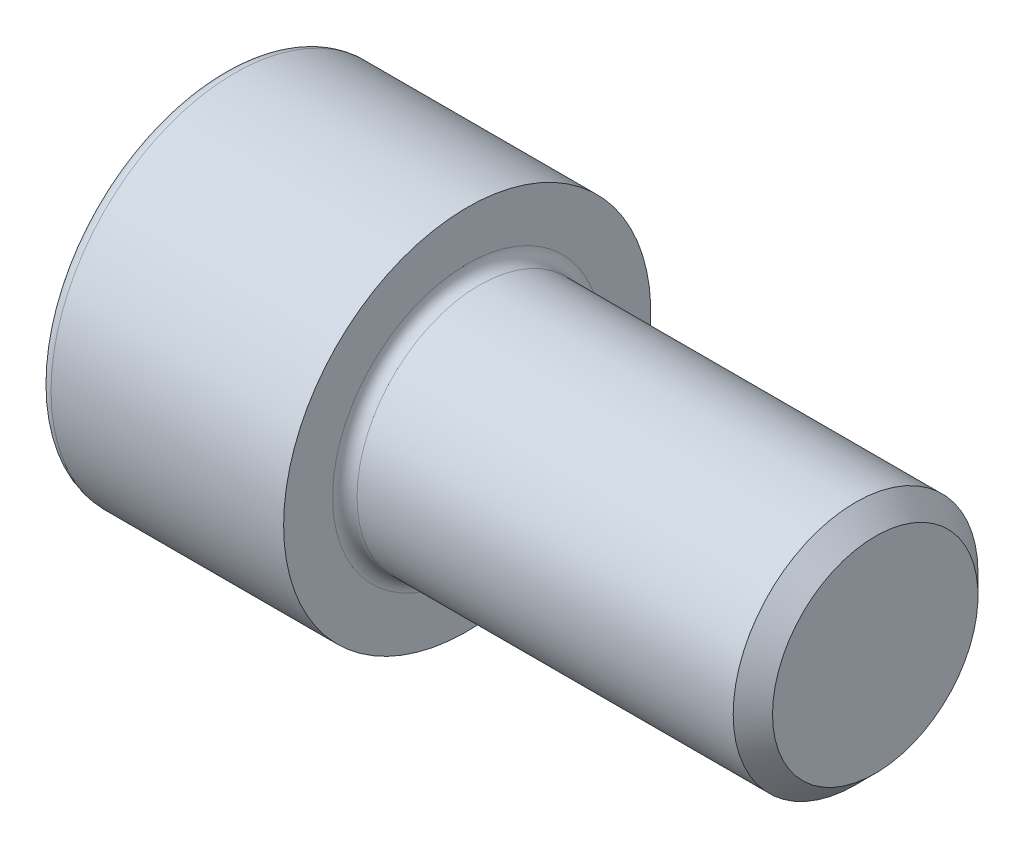
SolidWorks part; units mm, degrees
ref_plane "Plane1" through (0, 0, 0) normal (0, 0, 1) x (1, 0, 0)
ref_plane "Plane2" through (0, 0, 0) normal (0, 1, 0) x (1, 0, 0)
ref_plane "Plane3" through (0, 0, 0) normal (1, 0, 0) x (0, 0, -1)
sketch "BodySke" plane through (0, 0, 0) normal (0, 0, 1) x (1, 0, 0)
  line L0 (0, 0) -> (0, 9)
  line L1 (0, 9) -> (12, 9)
  line L2 (12, 9) -> (12, 6)
  line L3 (12, 6) -> (31.036, 6)
  line L4 (32, 5.036) -> (32, 0)
  line L5 (32, 0) -> (0, 0)
  line L6 (-31.75, 0) -> (127, 0) construction
  line L8 (32, 5.036) -> (31.036, 6)
  line L10 (32, -5.036) -> (31.036, -6) construction
  line L11 (13.75, 9.525) -> (13.75, 3.175) construction
  line L12 (12, 9.525) -> (12, 3.175) construction
  line L13 (-28, 9.525) -> (-28, 3.175) construction
  dimension "Diameter" = 12
  dimension "Head_ht" = 12
  dimension "Length" = 20
  dimension "Body_ch_ang" = 45
  dimension "Head_dia" = 18
  dimension "Minor_dia" = 10.072
  dimension "Advance" = 1.75
  dimension "Thread_nom" = 20
  dimension "Thread_length" = 60
revolve "Base-Revolve" add sketch "BodySke"
cosmetic thread "ThreadCosmetic" [suppressed]
fillet "Fillet1" radius 0.6 1 edges at (12, 0, 6)
fillet "Fillet2" radius 0.6 1 edges at (0, 0, 9)
sketch "Sketch2" plane through (0, 0, 0) normal (0, 0, 1) x (1, 0, 0)
  line L0 (0, 5.0575) -> (6, 5.0575)
  line L1 (6, 5.0575) -> (8.9199, 0)
  line L2 (-31.75, 0) -> (127, 0) construction
  line L3 (8.9199, 0) -> (0, 0)
  line L4 (0, 0) -> (0, 5.0575)
  line L6 (0, 0) -> (47.625, 0) construction
  dimension "D1" = 5.0575
  dimension "D2" = 60
  dimension "Depth" = 6
revolve "Hex-PreBroach" cut sketch "Sketch2" angle 360 about L6
sketch "Sketch3" plane through (0, 0, 0) normal (-1, 0, 0) x (0, 0.5, 0.866)
  line L0 (2.9199, 5.0575) -> (-2.9199, 5.0575)
  line L1 (-2.9199, 5.0575) -> (-5.8399, 0)
  line L2 (2.9199, 5.0575) -> (5.8399, 0)
  line L3 (2.9199, -5.0575) -> (5.8399, 0)
  line L4 (2.9199, -5.0575) -> (-2.9199, -5.0575)
  line L5 (-2.9199, -5.0575) -> (-5.8399, 0)
  dimension "D1" = 5.0575
  dimension "D2" = 5.0575
  dimension "Hex_size" = 10.115
extrude "Hex" cut sketch "Sketch3" against normal blind 6
sketch "ThdSchSke" plane through (0, 0, 0) normal (0, 0, 1) x (1, 0, 0)
  line L0 (17.25, -5.036) -> (16.575, -6)
  line L1 (17.25, -5.036) -> (17.925, -6)
  line L2 (17.925, -6) -> (17.925, -7.5)
  line L3 (-3.175, 0) -> (5.1513, 0) construction
  line L4 (0, 8.4) -> (0, -8.4) construction
  line L5 (17.925, -7.5) -> (16.575, -7.5)
  line L6 (16.575, -7.5) -> (16.575, -6)
  dimension "Thread_minor" = 10.072
  dimension "Diameter" = 12
  dimension "Start" = 17.25
  dimension "SideAngle" = 55
  dimension "VeeAngle" = 70
  dimension "Overcut" = 15
revolve "ThreadSchematic" [suppressed] cut sketch "ThdSchSke" angle 360 about L3
pattern_linear "ThdSchPat" [suppressed]
equation "\"D2@Sketch3\" = \"Hex_size@Sketch3\" / 2"
equation "\"D1@Sketch3\" = \"Hex_size@Sketch3\" / 2"
equation "\"D1@Sketch2\" = \"Hex_size@Sketch3\" / 2"
equation "\"Thread_minor@ThreadCosmetic\"  =  \"Minor_dia@BodySke\""
equation "\"Depth@Sketch2\" =  \"Key_eng@Hex\""
equation "\"Thread_length@ThreadCosmetic\" = ((sgn( (\"Length@BodySke\" - \"Advance@BodySke\" * 3.0) - \"Thread_nom@BodySke\" )-1)*( (\"Length@BodySke\" - \"Advance@BodySke\" * 3.0) - \"Thread_nom@BodySke\" ))/-2+ \"Thread_nom@BodySke\""
equation "\"Thread_minor@ThdSchSke\" = \"Minor_dia@BodySke\""
equation "\"Diameter@ThdSchSke\" = \"Diameter@BodySke\""
equation "\"Overcut@ThdSchSke\" = \"Diameter@BodySke\" * 1.25"
equation "\"Start@ThdSchSke\" = \"Head_ht@BodySke\" + \"Length@BodySke\" - \"Thread_length@ThreadCosmetic\"  '---Non-countersunk---"
equation "\"Num_threads@ThdSchPat\" = int( \"Thread_length@ThreadCosmetic\" / \"Advance@BodySke\" + 0.999 )  + 1"
equation "\"Advance@ThdSchPat\" = \"Thread_length@ThreadCosmetic\" /  (\"Num_threads@ThdSchPat\" - 1) 'relax it"
equation "\"Num_threads@ThdSchPat\" = \"Num_threads@ThdSchPat\" - sgn( \"Num_threads@ThdSchPat\" - 1) '---chamfered tips only---"
